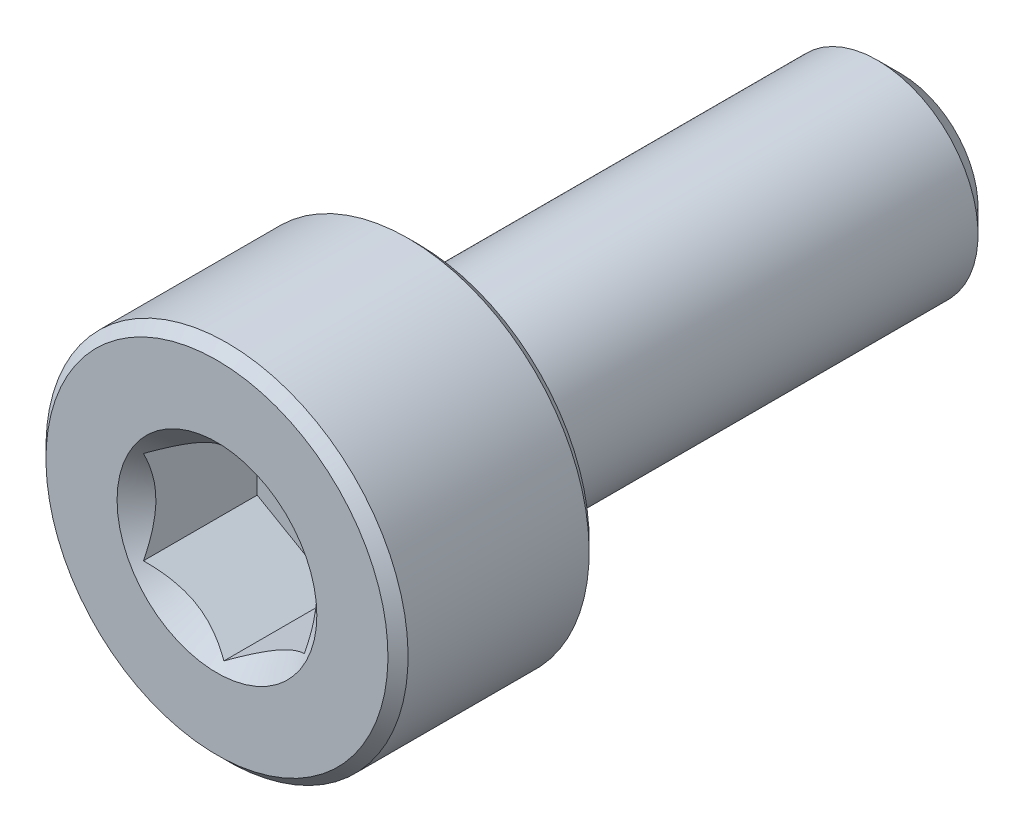
SolidWorks part; units mm, degrees
ref_plane "Front Plane" through (0, 0, 0) normal (0, 0, 1) x (1, 0, 0)
ref_plane "Top Plane" through (0, 0, 0) normal (0, 1, 0) x (1, 0, 0)
ref_plane "Right Plane" through (0, 0, 0) normal (1, 0, 0) x (0, 0, -1)
sketch "Sketch1" plane through (0, 0, 0) normal (1, 0, 0) x (0, 0, -1)
  line L0 (-4.25, 0) -> (4.25, 0) construction
  line L1 (4.25, 0) -> (4.25, 0.9577) construction
  line L2 (4.25, 0.9577) -> (3.9577, 1.25) construction
  line L3 (3.9577, 1.25) -> (3.9125, 1.25) construction
  line L4 (3.9125, 1.25) -> (-1.75, 1.25) construction
  line L5 (-1.75, 1.25) -> (-1.75, 2.25) construction
  line L6 (-1.75, 2.25) -> (-4.25, 2.25) construction
  line L7 (-4.25, 2.25) -> (-4.25, 0) construction
  line L8 (4.25, 0.9577) -> (4.25, 1.25) construction
  line L9 (4.2219, 1.2987) -> (4.4469, 0.909) construction
  line L10 (4.4469, 0.909) -> (4.6719, 1.2987) construction
  line L11 (4.6719, 1.2987) -> (4.2219, 1.2987) construction
  line L12 (4.4469, 1.2987) -> (4.4469, 1.25) construction
  line L13 (4.4469, 0.909) -> (4.4469, 0.9577) construction
  line L14 (4.4187, 0.9577) -> (4.475, 0.9577) construction
  line L15 (4.25, 1.25) -> (4.6437, 1.25) construction
  line L16 (4.2359, 1.2744) -> (4.6578, 1.2744) construction
  line L17 (4.25, 0) -> (4.25, -1.25) construction
  line L18 (-1.875, 2.25) -> (-1.75, 2.125) construction
  line L19 (-4.125, 2.25) -> (-4.25, 2.125) construction
  line L20 (-1.75, 1.25) -> (-1.75, 0) construction
  line L21 (-1.75, 0.625) -> (0.25, 0.625) construction
  line L22 (0.25, 0.625) -> (2.25, 0.625) construction
  line L23 (2.25, 0.625) -> (4.25, 0.625) construction
  line L24 (0.25, 0.625) -> (0.25, 1.25) construction
  line L25 (0.25, 1.25) -> (0.25, 2.25) construction
  line L26 (2.25, 0.625) -> (2.25, 2.25) construction
  point P0 (-4.25, 1)
  point P3 (3.125, 1.25)
  point P4 (0, 0)
  point P18 (2.25, 1.25)
  point P22 (4.4469, 0.9577)
  point P24 (3.9125, 1.25)
  point P25 (4.4469, 1.25)
  point P28 (4.4469, 1.2744)
  point P29 (3.125, -1.25)
  point P30 (0.25, 1.25)
  point P31 (-3, 2.25)
  point P37 (-2.1875, 2.25)
  point P38 (-4.0625, 2.25)
  point P45 (0.25, 0.625)
  point P46 (2.25, 0.625)
  dimension "D2" = 0.0563
  dimension "D7" = 0.125
  dimension "D8" = 0.125
  dimension "D9" = 0.125
  dimension "D10" = 0.0625
  dimension "D11" = 0.3125
  dimension "Drive Size" = 2
  dimension "Head Diameter" = 4.5
  dimension "Head Height" = 2.5
  dimension "Thread Pitch" = 0.45
  dimension "Thread Dia" = 2.5
  dimension "Length" = 6
  dimension "D12" = 0.3375
  dimension "D4" = 1.125
  dimension "D3" = 45
sketch "Sketch2" plane through (0, 0, 0) normal (1, 0, 0) x (0, 0, -1)
  line L0 (-4.25, 0) -> (-4.25, 2.125)
  line L1 (-4.125, 2.25) -> (-1.875, 2.25)
  line L2 (-1.75, 2.125) -> (-1.75, 1.375)
  line L4 (3.9577, 1.25) -> (4.25, 0.9577)
  line L5 (4.25, 0.9577) -> (4.25, 0)
  line L6 (-1.75, 2.25) -> (-4.25, 2.25) construction
  line L7 (4.25, 0) -> (-4.25, 0)
  line L8 (-4.125, 2.25) -> (-4.25, 2.125) construction
  line L10 (-4.125, 2.25) -> (-4.25, 2.125)
  line L14 (-1.875, 2.25) -> (-1.75, 2.125) construction
  line L16 (-1.875, 2.25) -> (-1.75, 2.125)
  line L17 (-1.75, 1.25) -> (-1.75, 2.25) construction
  line L19 (-1.625, 1.25) -> (3.9577, 1.25)
  line L20 (3.9125, 1.25) -> (-1.75, 1.25) construction
  arc A1 (-1.75, 1.375) -> (-1.625, 1.25) centre (-1.625, 1.375) ccw
  dimension "D3" = 0.125
revolve "Revolve1" add sketch "Sketch2" angle 360 about L7
sketch "Sketch3" plane through (0, 0, 4.25) normal (0, 0, 1) x (1, 0, 0)
  line L1 (1, -0.5774) -> (1, 0.5774)
  line L2 (1, 0.5774) -> (0, 1.1547)
  line L3 (0, 1.1547) -> (-1, 0.5774)
  line L4 (-1, 0.5774) -> (-1, -0.5774)
  line L5 (-1, -0.5774) -> (0, -1.1547)
  line L6 (0, -1.1547) -> (1, -0.5774)
  circle A0 centre (0, 0) radius 1 construction
  circle A1 centre (0, 0) radius 2.25 construction
  circle A2 centre (0, 0) radius 2.25 construction
  circle A3 centre (0, 0) radius 1.1547 construction
  point P13 (0, 0)
  dimension "D1" = 2.3094
extrude "Cut-Extrude1" cut sketch "Sketch3" against normal offset from surface (1.5 mm away) 1 up to face at (0, 2.125, 1.75)
sketch "Sketch4" plane through (0, 0, 4.25) normal (0, 0, 1) x (1, 0, 0)
  circle A0 centre (0, 0) radius 1.2413
  dimension "D1" = 2.4826
extrude "Cut-Extrude2" cut sketch "Sketch4" against normal up to vertex (1.25 mm away) draft 45 up to point (0, 2.25, 3)
sketch "Sketch11" plane through (0, 0, 0) normal (1, 0, 0) x (0, 0, -1)
  line L0 (-4.25, 0) -> (4.25, 0) construction
  line L1 (-4.25, 0) -> (4.25, 0) construction
  line L2 (-0.625, 0) -> (-0.625, 1.25) construction
  line L3 (3.9125, 1.25) -> (-1.75, 1.25) construction
  line L4 (3.125, 0) -> (3.125, 1.25) construction
  line L6 (4.25, 0.9577) -> (4.25, 1.25) construction
  point P2 (-0.625, 0)
  point P3 (3.125, 0)
  dimension "D1" = 1.125
  dimension "D2" = 1.125
sketch "Sketch6" plane through (0, 0, -4.25) normal (0, 0, -1) x (-1, 0, 0)
  circle A0 centre (0, 0) radius 1.25
curve "Helix/Spiral1" pitch 0.45 height 6.45 turns 14.3333
sketch "Sketch10" plane through (0, 0, 0) normal (1, 0, 0) x (0, 0, -1)
  line L0 (-1.625, -2.25) -> (-1.625, 2.25)
  line L5 (-4.25, 0) -> (4.25, 0) construction
  line L6 (-1.625, 1.25) -> (-1.625, -1.25) construction
  point P3 (-1.625, 0)
split "Split1" trim tools "Sketch10" bodies to split 106 resulting bodies 114 115
sketch "Sketch8" plane through (0, 0, 0) normal (1, 0, 0) x (0, 0, -1)
  line L0 (-1.75, 0) -> (-1.75, 1.25)
  line L1 (-1.625, -1.25) -> (-1.625, 1.25) construction
  line L2 (-1.75, 1.25) -> (-1.625, 1.25)
  line L4 (-1.625, 1.25) -> (-0.9033, 0)
  line L5 (-0.9033, 0) -> (-1.75, 0)
  line L6 (3.9125, 1.25) -> (-1.75, 1.25) construction
  line L7 (-4.25, 0) -> (4.25, 0) construction
  dimension "D1" = 60
revolve "Revolve2" add sketch "Sketch8" angle 360 about L5
equation "\"D2@Sketch1\" = \"Thread Pitch@Sketch1\" / 8"
equation "\"D4@Helix/Spiral1\" = \"Thread Pitch@Sketch1\""
equation "\"D7@Sketch1\" = \"Head Height@Sketch1\" * .05"
equation "\"D8@Sketch1\"=\"D7@Sketch1\""
equation "\"D9@Sketch1\"=\"D7@Sketch1\""
equation "\"D10@Sketch1\"=\"D7@Sketch1\"/2"
equation "\"D11@Sketch1\"=\"D10@Sketch1\"*5"
equation "\"D4@Sketch1\"=\"Thread Pitch@Sketch1\"*2.5"
equation "\"D12@Sketch1\"=\"Thread Pitch@Sketch1\"*.75"
equation "\"D3@Helix/Spiral1\"=\"Length@Sketch1\"+\"Thread Pitch@Sketch1\""
equation "\"D3@Sketch2\"=\"Thread Dia@Sketch1\"*0.05"
equation "\"D1@Sketch11\"=\"Length@Sketch1\"*0.1875"
equation "\"D2@Sketch11\"=\"D1@Sketch11\""
equation "\"D1@Sketch4\"=\"D1@Sketch3\"*1.075"
